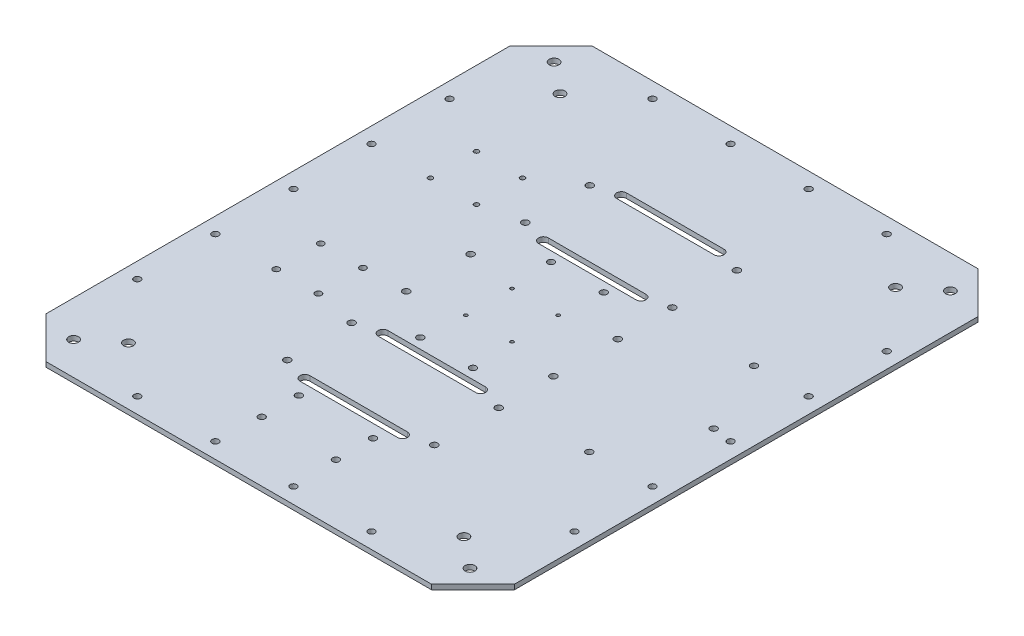
SolidWorks part; units mm, degrees
ref_plane "Front Plane" through (0, 0, 0) normal (0, 0, 1) x (1, 0, 0)
ref_plane "Top Plane" through (0, 0, 0) normal (0, 1, 0) x (1, 0, 0)
ref_plane "Right Plane" through (0, 0, 0) normal (1, 0, 0) x (0, 0, -1)
sketch "Sketch1" plane through (0, 0, 0) normal (0, 1, 0) x (1, 0, 0)
  line L0 (-121.2861, 96.1182) -> (-94.3453, 123.059)
  line L1 (-121.2861, 123.059) -> (183.5139, 123.059)
  line L2 (-121.2861, 123.059) -> (-121.2861, -232.541)
  line L3 (-121.2861, -232.541) -> (183.5139, -232.541)
  line L4 (183.5139, 123.059) -> (183.5139, -232.541)
  line L5 (31.1139, 95.069) -> (31.1139, -294.9418) construction
  line L6 (-146.0448, -54.741) -> (218.038, -54.741) construction
  line L7 (183.5139, 96.1182) -> (156.5732, 123.059)
  line L8 (183.5139, -205.6003) -> (156.5732, -232.541)
  line L9 (-121.2861, -205.6003) -> (-94.3453, -232.541)
  point P8 (31.1139, 123.059)
  point P11 (-121.2861, -54.741)
  point P18 (0, 0)
  dimension "D1" = 304.8
  dimension "D2" = 355.6
  dimension "D3" = 45
  dimension "D4" = 38.1
extrude "Boss-Extrude1" add sketch "Sketch1" along normal blind 3.175
sketch "Sketch2" plane through (0, 3.175, 0) normal (0, 1, 0) x (1, 0, 0)
  line L0 (31.1139, 123.059) -> (31.1139, -287.8465) construction
  line L1 (-94.3453, 123.059) -> (156.5732, 123.059) construction
  line L2 (183.5139, -54.741) -> (-158.2106, -54.741) construction
  line L3 (183.5139, 96.1182) -> (183.5139, -205.6003) construction
  circle A0 centre (13.8419, -12.069) radius 2.159
  circle A1 centre (48.1319, -12.069) radius 2.159
  circle A2 centre (13.8419, -97.159) radius 2.159
  circle A3 centre (48.1319, -97.159) radius 2.159
  dimension "D5" = 4.318
  dimension "D6" = 4.318
  dimension "D7" = 4.318
  dimension "D8" = 4.318
  dimension "D1" = 17.272
  dimension "D2" = 34.29
  dimension "D3" = 85.09
  dimension "D4" = 42.672
extrude "Cut-Extrude1" cut sketch "Sketch2" against normal through all
sketch "Sketch4" plane through (0, 3.175, 0) normal (0, 1, 0) x (1, 0, 0)
  line L0 (-0.6361, 48.256) -> (62.8639, 48.256) construction
  line L1 (-0.6361, 51.431) -> (62.8639, 51.431)
  line L2 (-0.6361, 45.081) -> (62.8639, 45.081)
  line L3 (-0.6361, -2.544) -> (62.8639, -2.544) construction
  line L4 (-0.6361, 0.631) -> (62.8639, 0.631)
  line L5 (-0.6361, -5.719) -> (62.8639, -5.719)
  line L6 (31.1139, 123.059) -> (31.1139, -75.2432) construction
  line L7 (-94.3453, 123.059) -> (156.5732, 123.059) construction
  line L8 (-121.2861, -54.741) -> (257.7387, -54.741) construction
  line L9 (-121.2861, 96.1182) -> (-121.2861, -205.6003) construction
  line L10 (31.1139, -232.541) -> (31.1139, -34.2388) construction
  line L11 (-0.6361, -106.938) -> (62.8639, -106.938) construction
  line L12 (-0.6361, -110.113) -> (62.8639, -110.113)
  line L13 (-0.6361, -103.763) -> (62.8639, -103.763)
  line L14 (-0.6361, -157.738) -> (62.8639, -157.738) construction
  line L15 (-0.6361, -160.913) -> (62.8639, -160.913)
  line L16 (-0.6361, -154.563) -> (62.8639, -154.563)
  arc A0 (-0.6361, 51.431) -> (-0.6361, 45.081) centre (-0.6361, 48.256) ccw
  arc A1 (62.8639, 45.081) -> (62.8639, 51.431) centre (62.8639, 48.256) ccw
  arc A2 (-0.6361, 0.631) -> (-0.6361, -5.719) centre (-0.6361, -2.544) ccw
  arc A3 (62.8639, -5.719) -> (62.8639, 0.631) centre (62.8639, -2.544) ccw
  circle A4 centre (48.1319, -12.069) radius 2.159 construction
  arc A5 (-0.6361, -110.113) -> (-0.6361, -103.763) centre (-0.6361, -106.938) cw
  arc A6 (62.8639, -103.763) -> (62.8639, -110.113) centre (62.8639, -106.938) cw
  arc A7 (-0.6361, -160.913) -> (-0.6361, -154.563) centre (-0.6361, -157.738) cw
  arc A8 (62.8639, -154.563) -> (62.8639, -160.913) centre (62.8639, -157.738) cw
  point P2 (31.1139, 48.256)
  point P7 (31.1139, -2.544)
  point P28 (31.1139, -106.938)
  point P35 (31.1139, -157.738)
  dimension "D1" = 63.5
  dimension "D2" = 63.5
  dimension "D3" = 6.35
  dimension "D4" = 6.35
  dimension "D5" = 44.45
  dimension "D6" = 6.35
extrude "Cut-Extrude2" cut sketch "Sketch4" against normal through all
sketch "Sketch7" plane through (0, 3.175, 0) normal (0, 1, 0) x (1, 0, 0)
  line L0 (-57.7861, 57.7696) -> (-57.7861, -55.8318) construction
  line L1 (-121.2861, -54.741) -> (183.5139, -54.741) construction
  line L2 (-121.2861, 96.1182) -> (-121.2861, -205.6003) construction
  line L3 (183.5139, 96.1182) -> (183.5139, -205.6003) construction
  circle A0 centre (-42.8001, 26.031) radius 1.524
  circle A1 centre (-42.8001, -3.941) radius 1.524
  circle A2 centre (-72.7721, -3.941) radius 1.524
  circle A3 centre (-72.7721, 26.031) radius 1.524
  dimension "D1" = 3.048
  dimension "D2" = 14.986
  dimension "D4" = 29.972
  dimension "D3" = 3.048
  dimension "D5" = 50.8
  dimension "D6" = 63.5
  dimension "D7" = 14.986
extrude "Cut-Extrude3" cut sketch "Sketch7" against normal through all
sketch "Sketch8" plane through (0, 3.175, 0) normal (0, 1, 0) x (1, 0, 0)
  line L0 (-94.3453, -232.541) -> (156.5732, -232.541) construction
  line L1 (183.5139, 96.1182) -> (183.5139, -205.6003) construction
  circle A0 centre (73.0239, -207.649) radius 1.524
  circle A1 centre (73.0239, -177.169) radius 1.524
  circle A2 centre (96.8999, -207.649) radius 1.524
  circle A3 centre (96.8999, -177.169) radius 1.524
  dimension "D1" = 3.048
  dimension "D2" = 30.48
  dimension "D3" = 23.876
  dimension "D4" = 24.892
  dimension "D5" = 86.614
extrude "Cut-Extrude4" [suppressed] cut sketch "Sketch8" against normal through all and the other way through all
sketch "Sketch10" plane through (0, 0, 0) normal (0, -1, 0) x (1, 0, 0)
  line L0 (-94.3453, 232.541) -> (156.5732, 232.541) construction
  line L1 (31.1139, 232.541) -> (31.1139, 128.7119) construction
  circle A0 centre (6.9839, 193.4758) radius 2.159
  circle A1 centre (55.2439, 193.4758) radius 2.159
  circle A2 centre (6.9839, 169.3458) radius 2.159
  circle A3 centre (55.2439, 169.3458) radius 2.159
  dimension "D1" = 4.318
  dimension "D2" = 48.26
  dimension "D4" = 39.0652
  dimension "D6" = 4.318
  dimension "D7" = 4.318
  dimension "D8" = 4.318
  dimension "D3" = 24.13
  dimension "D5" = 24.13
extrude "Cut-Extrude6" cut sketch "Sketch10" against normal through all
sketch "Sketch9" plane through (0, 0, 0) normal (0, -1, 0) x (-1, 0, 0)
  line L0 (94.3453, -232.541) -> (-156.5732, -232.541) construction
  line L2 (57.7861, -47.3693) -> (57.7861, -130.2963) construction
  line L3 (-156.5732, -232.541) -> (-192.4942, -196.62) construction
  line L4 (-156.5732, -232.541) -> (-120.6522, -196.62) construction
  line L5 (-120.6522, -196.62) -> (-156.5732, -160.699) construction
  line L6 (-192.4942, -196.62) -> (-156.5732, -160.699) construction
  line L7 (121.2861, 96.1182) -> (121.2861, -205.6003) construction
  line L8 (-183.5139, -205.6003) -> (-156.5732, -232.541) construction
  circle A0 centre (71.5021, -105.541) radius 2.032
  circle A1 centre (44.0701, -105.541) radius 2.032
  circle A2 centre (71.5021, -76.585) radius 2.032
  circle A3 centre (44.0701, -76.585) radius 2.032
  dimension "D1" = 4.064
  dimension "D9" = 4.064
  dimension "D2" = 63.5
  dimension "D3" = 28.956
  dimension "D4" = 127
  dimension "D6" = 50.8
  dimension "D7" = 50.8
  dimension "D8" = 13.716
extrude "Cut-Extrude5" cut sketch "Sketch9" against normal through all
sketch "Sketch13" plane through (0, 0, 0) normal (0, -1, 0) x (1, 0, 0)
  line L0 (31.1139, -123.059) -> (31.1139, 261.4711) construction
  line L1 (-94.3453, -123.059) -> (156.5732, -123.059) construction
  line L2 (-121.2861, 54.741) -> (239.2508, 54.741) construction
  line L3 (-121.2861, -96.1182) -> (-121.2861, 205.6003) construction
  circle A0 centre (16.1139, 69.741) radius 1.1
  circle A1 centre (16.1139, 39.741) radius 1.1
  circle A2 centre (46.1139, 39.741) radius 1.1
  circle A3 centre (46.1139, 69.741) radius 1.1
  dimension "D1" = 2.2
  dimension "D2" = 2.2
  dimension "D3" = 30
  dimension "D4" = 15
  dimension "D5" = 15
extrude "Cut-Extrude8" cut sketch "Sketch13" against normal through all
sketch "Sketch14" plane through (0, 0, 0) normal (0, -1, 0) x (1, 0, 0)
  line L0 (31.1139, 232.541) -> (31.1139, -154.5354) construction
  line L1 (-94.3453, 232.541) -> (156.5732, 232.541) construction
  line L2 (-121.2861, 54.741) -> (331.9066, 54.741) construction
  line L3 (-121.2861, -96.1182) -> (-121.2861, 205.6003) construction
  line L4 (-121.2861, 205.6003) -> (-94.3453, 232.541) construction
  line L5 (-236.5662, -212.9391) -> (298.794, 322.4211) construction
  line L6 (-236.5662, -212.9391) -> (298.794, -212.9391) construction
  line L7 (-236.5662, -212.9391) -> (-236.5662, 322.4211) construction
  line L8 (-121.2861, 205.6003) -> (-94.3453, 232.541) construction
  line L9 (-107.8157, 219.0706) -> (-42.2521, 166.4415) construction
  line L10 (-236.5662, 322.4211) -> (298.794, 322.4211) construction
  line L11 (298.794, -212.9391) -> (298.794, 322.4211) construction
  line L12 (298.794, -212.9391) -> (-236.5662, 322.4211) construction
  line L14 (-121.2861, -96.1182) -> (-94.3453, -123.059) construction
  line L21 (-236.5662, -212.9391) -> (-107.8157, -109.5886) construction
  line L22 (170.0436, -109.5886) -> (298.794, -212.9391) construction
  line L23 (183.5139, -96.1182) -> (156.5732, -123.059) construction
  line L24 (170.0436, 219.0706) -> (298.794, 322.4211) construction
  line L25 (183.5139, 205.6003) -> (156.5732, 232.541) construction
  line L26 (-236.5662, 322.4211) -> (-107.8157, 219.0706) construction
  circle A1 centre (-97.8527, 211.0731) radius 3.175
  circle A3 centre (-78.0449, 195.1731) radius 3.175
  circle A4 centre (140.2728, 195.1731) radius 3.175
  circle A7 centre (160.0806, 211.0731) radius 3.175
  circle A8 centre (-97.8527, -101.5911) radius 3.175
  circle A11 centre (-78.0449, -85.691) radius 3.175
  circle A14 centre (160.0806, -101.5911) radius 3.175
  circle A15 centre (140.2728, -85.691) radius 3.175
  point P8 (31.1139, 54.741)
  point P30 (298.794, 54.741)
  point P33 (-107.8157, -109.5886)
  point P36 (31.1139, -212.9391)
  dimension "D3" = 6.35
  dimension "D6" = 6.35
  dimension "D1" = 12.7
  dimension "D2" = 165.1
  dimension "D9" = 25.4
extrude "Cut-Extrude9" cut sketch "Sketch14" against normal through all
sketch "Sketch15" plane through (0, 0, 0) normal (0, -1, 0) x (1, 0, 0)
  line L0 (31.1139, 232.541) -> (31.1139, 125.875) construction
  line L1 (-94.3453, 232.541) -> (156.5732, 232.541) construction
  line L2 (-121.2861, 54.741) -> (75.4631, 54.741) construction
  line L3 (-121.2861, -96.1182) -> (-121.2861, 205.6003) construction
  circle A0 centre (5.7139, 222.381) radius 2.159
  circle A1 centre (-45.0861, 222.381) radius 2.159
  circle A2 centre (-111.1261, 54.741) radius 2.159
  circle A3 centre (-111.1261, 105.541) radius 2.159
  circle A4 centre (-111.1261, 156.341) radius 2.159
  circle A5 centre (173.3539, 156.341) radius 2.159
  circle A6 centre (173.3539, 105.541) radius 2.159
  circle A7 centre (173.3539, 54.741) radius 2.159
  circle A8 centre (107.3139, 222.381) radius 2.159
  circle A9 centre (56.5139, 222.381) radius 2.159
  circle A10 centre (56.5139, -112.899) radius 2.159
  circle A11 centre (107.3139, -112.899) radius 2.159
  circle A12 centre (173.3539, 3.941) radius 2.159
  circle A13 centre (173.3539, -46.859) radius 2.159
  circle A14 centre (-111.1261, -46.859) radius 2.159
  circle A15 centre (-111.1261, 3.941) radius 2.159
  circle A16 centre (-45.0861, -112.899) radius 2.159
  circle A17 centre (5.7139, -112.899) radius 2.159
  dimension "D3" = 4.318
  dimension "D4" = 4.318
  dimension "D8" = 4.318
  dimension "D9" = 4.318
  dimension "D10" = 4.318
  dimension "D1" = 25.4
  dimension "D2" = 50.8
  dimension "D5" = 10.16
  dimension "D6" = 50.8
  dimension "D7" = 50.8
  dimension "D11" = 10.16
extrude "Cut-Extrude10" cut sketch "Sketch15" against normal through all
sketch "Sketch16" plane through (0, 0, 0) normal (0, -1, 0) x (-1, 0, 0)
  line L1 (-103.7737, -99.6794) -> (-153.6537, -99.6794)
  line L2 (-103.7737, -99.6794) -> (-103.7737, -11.5294)
  line L3 (-103.7737, -11.5294) -> (-153.6537, -11.5294)
  line L4 (-153.6537, -99.6794) -> (-153.6537, -11.5294)
  line L5 (-183.5139, 96.1182) -> (-183.5139, -205.6003) construction
  circle A0 centre (-133.3337, -106.6794) radius 2.159
  circle A1 centre (-138.4137, -4.5294) radius 2.159
  circle A2 centre (-160.6539, -53.0294) radius 2.159
  dimension "D3" = 7
  dimension "D4" = 7.0002
  dimension "D5" = 7
  dimension "D6" = 20.32
  dimension "D7" = 15.24
  dimension "D8" = 46.65
  dimension "D9" = 4.318
  dimension "D10" = 4.318
  dimension "D11" = 4.318
  dimension "D1" = 88.15
  dimension "D2" = 49.88
  dimension "D12" = 22.86
extrude "Cut-Extrude11" cut sketch "Sketch16" against normal through all contours A2 | A0 | A1
sketch "Sketch17" plane through (0, 3.175, 0) normal (0, 1, 0) x (1, 0, 0)
  line L2 (31.1139, 123.059) -> (31.1139, -395.818) construction
  line L3 (-94.3453, 123.059) -> (156.5732, 123.059) construction
  line L4 (183.5139, -54.741) -> (-127.1454, -54.741) construction
  line L5 (183.5139, 96.1182) -> (183.5139, -205.6003) construction
  line L6 (-94.3453, -232.541) -> (156.5732, -232.541) construction
  circle A12 centre (78.9929, -153.166) radius 2.2225
  circle A13 centre (-16.7651, -153.166) radius 2.2225
  circle A14 centre (78.9929, -111.256) radius 2.2225
  circle A15 centre (-16.7651, -111.256) radius 2.2225
  circle A16 centre (78.9929, -75.696) radius 2.2225
  circle A17 centre (-16.7651, -75.696) radius 2.2225
  circle A18 centre (78.9929, -33.786) radius 2.2225
  circle A19 centre (-16.7651, -33.786) radius 2.2225
  circle A20 centre (78.9929, 1.774) radius 2.2225
  circle A21 centre (-16.7651, 1.774) radius 2.2225
  circle A22 centre (78.9929, 43.684) radius 2.2225
  circle A23 centre (-16.7651, 43.684) radius 2.2225
  circle A24 centre (-16.7651, 43.684) radius 2.2225
  circle A25 centre (78.9929, 43.684) radius 2.2225
  circle A26 centre (-16.7651, 1.774) radius 2.2225
  circle A27 centre (78.9929, 1.774) radius 2.2225
  circle A28 centre (-16.7651, -33.786) radius 2.2225
  circle A29 centre (78.9929, -33.786) radius 2.2225
  circle A30 centre (-16.7651, -75.696) radius 2.2225
  circle A31 centre (78.9929, -75.696) radius 2.2225
  circle A32 centre (-16.7651, -111.256) radius 2.2225
  circle A33 centre (78.9929, -111.256) radius 2.2225
  circle A34 centre (-16.7651, -153.166) radius 2.2225
  point P21 (0, 0)
  point P23 (0, 0)
  point P47 (0, 0)
  point P48 (0, 0)
  point P49 (0, 0)
  point P50 (0, 0)
  point P51 (0, 0)
  point P52 (0, 0)
  dimension "D1" = 4.445
  dimension "D2" = 4.445
  dimension "D3" = 4.445
  dimension "D4" = 4.445
  dimension "D5" = 4.445
  dimension "D6" = 4.445
  dimension "D7" = 4.445
  dimension "D8" = 4.445
  dimension "D9" = 4.445
  dimension "D10" = 4.445
  dimension "D11" = 4.445
  dimension "D12" = 4.445
  dimension "D13" = 95.758
  dimension "D14" = 41.91
  dimension "D15" = 95.758
  dimension "D16" = 41.91
  dimension "D17" = 95.758
  dimension "D18" = 41.91
  dimension "D19" = 47.879
  dimension "D20" = 47.879
  dimension "D21" = 47.879
  dimension "D22" = 20.955
  dimension "D23" = 79.375
  dimension "D24" = 79.375
extrude "Cut-Extrude13" cut sketch "Sketch17" against normal through all contours A23 | A22 | A20 | A21 | A18 | A19 | A17 | A16 | A12 | A14 | A15 | A13
